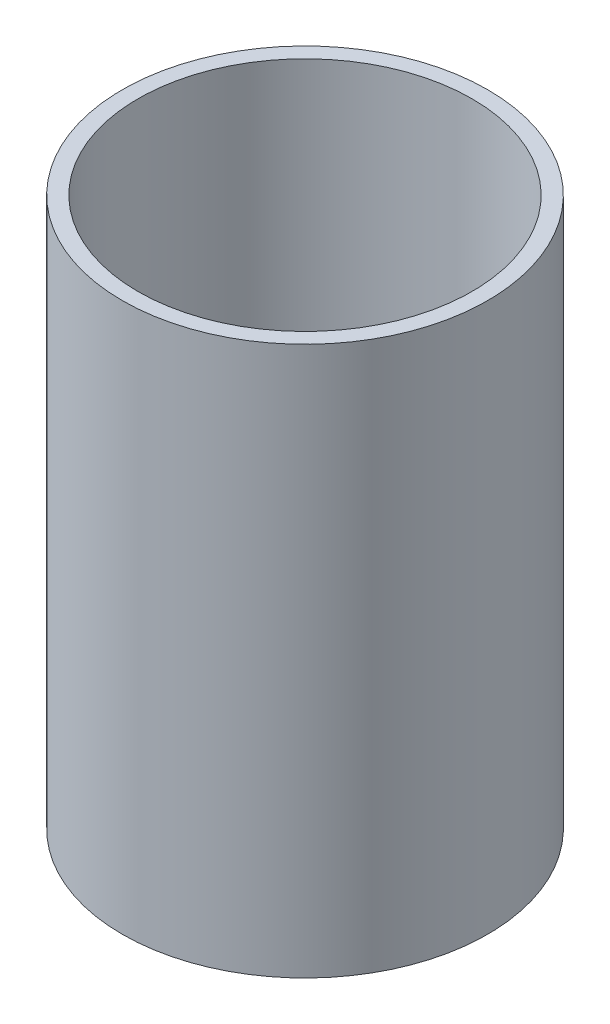
SolidWorks part; units mm, degrees
material "6061 Alloy"
ref_plane "Front Plane" through (0, 0, 0) normal (0, 0, 1) x (1, 0, 0)
ref_plane "Top Plane" through (0, 0, 0) normal (0, 1, 0) x (1, 0, 0)
ref_plane "Right Plane" through (0, 0, 0) normal (1, 0, 0) x (0, 0, -1)
sketch "Sketch1" plane through (0, 0, 0) normal (0, 1, 0) x (0.9991, 0, -0.0422)
  circle A0 centre (28.5429, 18.9571) radius 10.65
  circle A1 centre (28.5429, 18.9571) radius 11.65
  dimension "D1" = 1
extrude "Boss-Extrude1" add sketch "Sketch1" along normal blind 35
